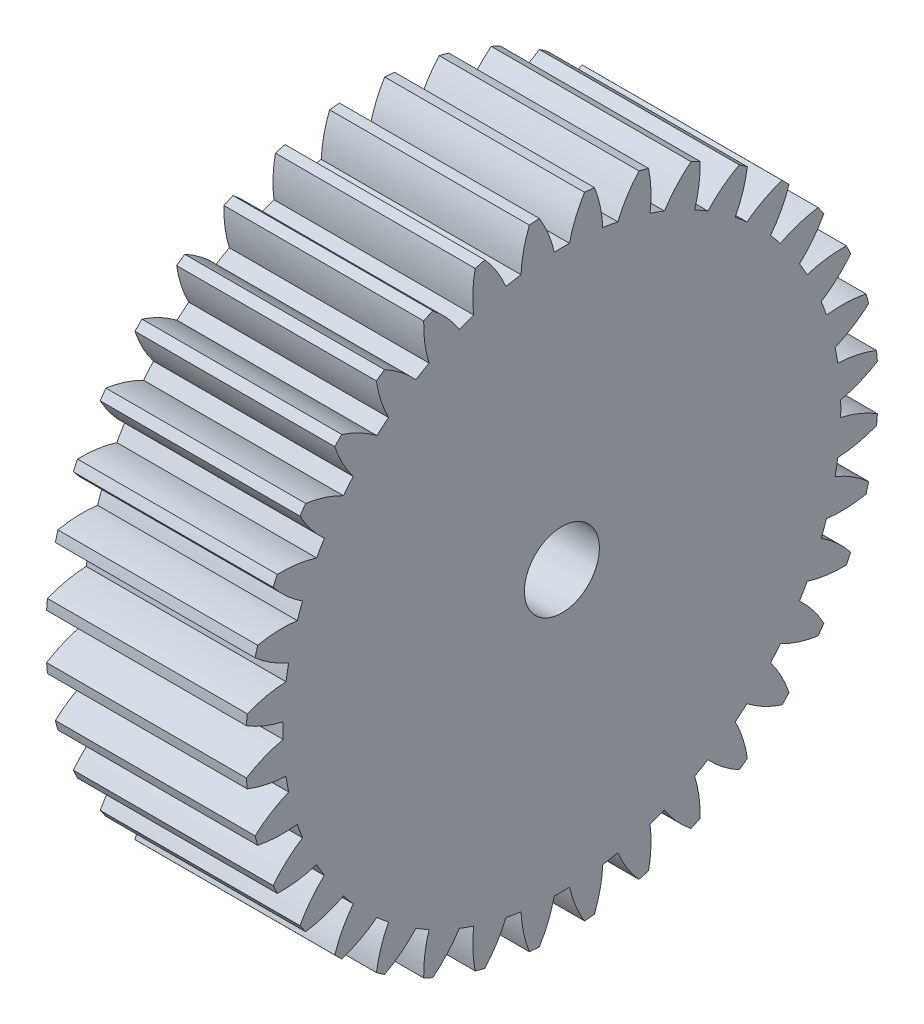
SolidWorks part; units mm, degrees
ref_plane "Plane1" through (0, 0, 0) normal (0, 0, 1) x (1, 0, 0)
ref_plane "Plane2" through (0, 0, 0) normal (0, 1, 0) x (1, 0, 0)
ref_plane "Plane3" through (0, 0, 0) normal (1, 0, 0) x (0, 0, -1)
other "Configuration Table"
sketch "HoldingSke" plane through (0, 0, 0) normal (0, 1, 0) x (1, 0, 0)
  line L0 (0, 0) -> (493.1768, -358.3139)
  line L1 (-15, 0) -> (100, 0) construction
  line L2 (0, 0) -> (-2.1039, 2.3779)
  line L3 (0, 0) -> (-11.863, 4.5341)
  line L4 (0, 0) -> (6.9867, 5.0761)
  line L5 (0, 0) -> (-47.5972, -17.7524)
  line L6 (0, 0) -> (-10.5278, -7.1032)
  line L7 (-2.1039, 2.3779) -> (8.8308, 51.9871)
  line L8 (-76.2, 54.61) -> (-71.1708, 54.61)
  line L9 (-71.009, 38.7566) -> (-53.1078, 45.2721)
  line L10 (-76.2, 71.12) -> (104.1128, 71.12)
  line L11 (0, 0) -> (-12.7, 0)
  line L12 (-76.2, 101.6) -> (-76.1573, 101.6)
  line L13 (24.9733, 27.94) -> (52.9518, 28.4284)
  line L14 (24.9733, 27.94) -> (25.0241, 27.9398)
  line L15 (24.9733, 27.94) -> (100.4021, 29.52)
  circle A0 centre (0, 0) radius 2.3812
  circle A1 centre (0, 0) radius 17.7292
  circle A2 centre (0, 0) radius 38.1
  circle A3 centre (0, 0) radius 2.3812
  dimension "MHD" = 35.4584
  dimension "Hub_dia" = 76.2
  dimension "Bore" = 4.7625
  dimension "MBD" = 4.7625
  dimension "Num_teeth" = 36
  dimension "Pitch" = 609.6
  dimension "Overall_len" = 50.8
  dimension "Show_teeth" = 36
  dimension "Thickness" = 12.7
  dimension "OAL" = 50.8001
  dimension "T_dim" = 5.0292
  dimension "Ap" = 20
  dimension "H" = 19.05
  dimension "Pitch_radius" = 180.3128
  dimension "Width" = 12.7
  dimension "Backlash" = 0.0427
  dimension "Addendum_fac" = 1
  dimension "Dedendum_fac" = 1.2
  dimension "Clearance_fac" = 0.2
  dimension "Dedendum_add" = 0.0508
sketch "BasProSke" plane through (0, 0, 0) normal (0, 1, 0) x (1, 0, 0)
  line L0 (-10, 0) -> (60, 0) construction
  line L1 (0, 0) -> (0, 20.1083)
  line L2 (0, 0) -> (12.7, 0)
  line L3 (12.7, 0) -> (12.7, 20.1083)
  line L4 (12.7, 20.1083) -> (0, 20.1083)
  dimension "Thickness" = 12.7
  dimension "Diameter" = 40.2167
revolve "Base-Revolve" add sketch "BasProSke" angle 360 about L0
sketch "TooCutSke" plane through (0, 0, 0) normal (1, 0, 0) x (0, 0, -1)
  line L1 (0, 0) -> (0, 107) construction
  line L2 (0, 0) -> (-0.9056, 19.0285) construction
  line L3 (0, 0) -> (-3.318, 37.9251) construction
  line L4 (-0.9056, 19.0285) -> (-1.659, 18.9625) construction
  arc A0 (0.4859, 17.7225) -> (-0.4859, 17.7225) centre (0, 0) ccw
  arc A1 (1.4524, 20.0813) -> (-1.4524, 20.0813) centre (0, 0) ccw
  circle A2 centre (0, 0) radius 19.05 construction
  circle A3 centre (0, 0) radius 17.9011 construction
  arc A4 (-0.4859, 17.7225) -> (-1.4524, 20.0813) centre (-7.9208, 16.0534) ccw
  arc A5 (1.4524, 20.0813) -> (0.4859, 17.7225) centre (7.9208, 16.0534) ccw
  dimension "Root_dia" = 35.4584
  dimension "Overcut_dia" = 40.2675
  dimension "Pitch_dia" = 38.1
  dimension "Base_dia" = 35.8023
  dimension "Flank_rad" = 7.62
  dimension "Half_ang" = 5
  dimension "Half_CT" = 0.7563
extrude "ToothCut" cut sketch "TooCutSke" along normal through all
fillet "Breaks" [suppressed] radius 0.0212
fillet "RootFillets" [suppressed] radius 0.2625
pattern_circular "TeethCuts" count 36 every 10 about axis through (-10, 0, 0) along (1, 0, 0) of "ToothCut", "RootFillets", "Breaks"
sketch "HubNeaOneSke" plane through (0, 0, 0) normal (-1, 0, 0) x (0, 0, 1)
  circle A0 centre (0, 0) radius 17.7292
  dimension "Diameter" = 35.4584
extrude "HubNearOne" [suppressed] add sketch "HubNeaOneSke" along normal blind 38.1001
sketch "HubNeaBotSke" plane through (0, 0, 0) normal (-1, 0, 0) x (0, 0, 1)
  circle A0 centre (0, 0) radius 17.7292
  dimension "Diameter" = 35.4584
extrude "HubNearBoth" [suppressed] add sketch "HubNeaBotSke" along normal blind 19.05
ref_plane "FarPln" through (12.7, 0, 0) normal (1, 0, 0) x (0, 0, -1)
sketch "HubFarSke" plane through (12.7, 0, 0) normal (1, 0, 0) x (0, 0, -1)
  circle A0 centre (0, 0) radius 17.7292
  dimension "Diameter" = 35.4584
extrude "HubFar" [suppressed] add sketch "HubFarSke" along normal blind 19.05
sketch "BorSke" plane through (0, 0, 0) normal (1, 0, 0) x (0, 0, -1)
  circle A0 centre (0, 0) radius 2.3812
  dimension "Diameter" = 4.7625
extrude "Bore" cut sketch "BorSke" along normal mid plane 101.6001
sketch "KeySke" plane through (0, 0, 0) normal (1, 0, 0) x (0, 0, -1)
  line L0 (-0.127, 0) -> (-0.127, 2.6479)
  line L1 (-0.127, 2.6479) -> (0.127, 2.6479)
  line L2 (0.127, 2.6479) -> (0.127, 0)
  line L3 (0, 0) -> (0, 34) construction
  line L4 (-0.127, 0) -> (0.127, 0)
  dimension "Offset" = 2.648
  dimension "Width" = 0.254
extrude "Keyway" [suppressed] cut sketch "KeySke" along normal mid plane 101.6001
pattern_circular "Keyway2" [suppressed] count 2 every 90 about axis through (-10, 0, 0) along (1, 0, 0)
equation "' \"Pitch@HoldingSke\" = 4"
equation "' \"Num_teeth@HoldingSke\" = 12"
equation "' \"Ap@HoldingSke\" =  20"
equation "' \"Ap@HoldingSke\" = 20"
equation "' \"Width@HoldingSke\" = 0.5"
equation "' \"Hub_dia@HoldingSke\"= 1"
equation "' \"Hub_dia@HoldingSke\" = 1"
equation "' \"Overall_len@HoldingSke\" = 1.0"
equation "' \"Bore@HoldingSke\" = 0.75"
equation "' \"T_dim@HoldingSke\" = 0.85"
equation "' \"Width@KeySke\" = 0.25"
equation "' \"Show_teeth@HoldingSke\" = 13"
equation "' \"Backlash@HoldingSke\" = 0.009"
equation "' \"Addendum_fac@HoldingSke\" = 1.0"
equation "' \"Dedendum_fac@HoldingSke\" = 1.25"
equation "' \"Dedendum_add@HoldingSke\" = 0.00005"
equation "' \"Clearance_fac@HoldingSke\" = 0.25"
equation "' \"Pitch@HoldingSke\" = 0.5"
equation "' \"Num_teeth@HoldingSke\" = 23"
equation "' \"Show_teeth@HoldingSke\" = 23"
equation "' \"Backlash@HoldingSke\" = 0.0375"
equation "\"Overcut_dia@TooCutSke\" = (\"Num_teeth@HoldingSke\" + 2 * \"Addendum_fac@HoldingSke\") / \"Pitch@HoldingSke\" + 0.002"
equation "\"Pitch_dia@TooCutSke\" = \"Num_teeth@HoldingSke\" / \"Pitch@HoldingSke\""
equation "\"Base_dia@TooCutSke\" = \"Num_teeth@HoldingSke\" / \"Pitch@HoldingSke\" * cos((\"Ap@HoldingSke\"  * 3.14159265 / 180))"
equation "\"Root_dia@TooCutSke\" = (\"Num_teeth@HoldingSke\" + 2) / \"Pitch@HoldingSke\" - 2 * (\"Addendum_fac@HoldingSke\" + \"Dedendum_fac@HoldingSke\") / \"Pitch@HoldingSke\" - \"Dedendum_add@HoldingSke\" * 2"
equation "\"Half_ang@TooCutSke\" = 180 / \"Num_teeth@HoldingSke\""
equation "\"Half_CT@TooCutSke\" = \"Num_teeth@HoldingSke\" / \"Pitch@HoldingSke\" * sin((3.14159265 / 2 / \"Num_teeth@HoldingSke\")) / 2 - 7 * \"Backlash@HoldingSke\" / 4"
equation "\"Flank_rad@TooCutSke\" = \"Num_teeth@HoldingSke\" / \"Pitch@HoldingSke\" / 5"
equation "\"Radius@RootFillets\" = \"Clearance_fac@HoldingSke\" / \"Pitch@HoldingSke\" + \"Dedendum_add@HoldingSke\""
equation "\"Break_rad@Breaks\" = 0.02 / \"Pitch@HoldingSke\""
equation "\"Thickness@HoldingSke\" = \"Width@HoldingSke\""
equation "\"OAL@HoldingSke\" = \"Thickness@HoldingSke\""
equation "\"MHD@HoldingSke\" = (\"Num_teeth@HoldingSke\" + 2) / \"Pitch@HoldingSke\" - 2 * (\"Addendum_fac@HoldingSke\" + \"Dedendum_fac@HoldingSke\")  / \"Pitch@HoldingSke\" - \"Dedendum_add@HoldingSke\" * 2"
equation "\"MBD@HoldingSke\" = (\"Num_teeth@HoldingSke\" + 2) / \"Pitch@HoldingSke\" - 2 * (\"Addendum_fac@HoldingSke\" + \"Dedendum_fac@HoldingSke\")  / \"Pitch@HoldingSke\" - \"Dedendum_add@HoldingSke\" * 2 - 0.002"
equation "\"MHD@HoldingSke\" = ((sgn( \"MHD@HoldingSke\" - \"Hub_dia@HoldingSke\" )-1)*( \"MHD@HoldingSke\" - \"Hub_dia@HoldingSke\" ))/-2+ \"Hub_dia@HoldingSke\""
equation "\"MBD@HoldingSke\" = ((sgn( \"MBD@HoldingSke\" - \"Bore@HoldingSke\" )-1)*( \"MBD@HoldingSke\" - \"Bore@HoldingSke\" ))/-2+ \"Bore@HoldingSke\""
equation "\"OAL@HoldingSke\" = ((sgn( \"OAL@HoldingSke\" - \"Overall_len@HoldingSke\" )+1)*( \"OAL@HoldingSke\" - \"Overall_len@HoldingSke\" ))/2 + \"Overall_len@HoldingSke\" + 0.000002"
equation "\"Num_teeth@TeethCuts\" = int( \"Show_teeth@HoldingSke\" ) + 1"
equation "\"Num_teeth@TeethCuts\" = ((sgn( \"Num_teeth@TeethCuts\" - \"Num_teeth@HoldingSke\" )-1)*( \"Num_teeth@TeethCuts\" - \"Num_teeth@HoldingSke\" ))/-2+ \"Num_teeth@HoldingSke\""
equation "\"Num_teeth@TeethCuts\" = ((sgn( \"Num_teeth@TeethCuts\" - 2.0)+1)*( \"Num_teeth@TeethCuts\" - 2.0))/2 +2.0"
equation "\"Angle@TeethCuts\" = 360.0 / \"Num_teeth@HoldingSke\""
equation "\"Diameter@BasProSke\" = (\"Num_teeth@HoldingSke\" + 2 * \"Addendum_fac@HoldingSke\") / \"Pitch@HoldingSke\""
equation "\"Thickness@BasProSke\"  = \"Thickness@HoldingSke\""
equation "' \"Fillet_rad@BasProSke\" =  \"Thickness@HoldingSke\" * 0.05"
equation "' \"Fillet_rad@BasProSke\" = \"Thickness@HoldingSke\" * 0.05"
equation "\"MHD@HoldingSke\" = ((sgn( \"MHD@HoldingSke\" - \"Root_dia@TooCutSke\" )-1)*( \"MHD@HoldingSke\" - \"Root_dia@TooCutSke\" ))/-2+ \"Root_dia@TooCutSke\""
equation "\"Diameter@HubNeaOneSke\" = \"MHD@HoldingSke\""
equation "\"Length@HubNearOne\" = \"OAL@HoldingSke\" - \"Thickness@BasProSke\""
equation "\"Diameter@HubNeaBotSke\" = \"MHD@HoldingSke\""
equation "\"Length@HubNearBoth\" = ( \"OAL@HoldingSke\" - \"Thickness@BasProSke\" ) / 2.0"
equation "\"Thickness@FarPln\" = \"Thickness@BasProSke\""
equation "\"Diameter@HubFarSke\" = \"MHD@HoldingSke\""
equation "\"Length@HubFar\" = ( \"OAL@HoldingSke\" - \"Thickness@BasProSke\" ) / 2.0"
equation "\"Diameter@BorSke\" = \"MBD@HoldingSke\""
equation "\"D1@Bore\" = \"OAL@HoldingSke\" * 2.0"
equation "\"D1@Keyway\" = \"OAL@HoldingSke\" * 2.0"
equation "\"Offset@KeySke\" = \"T_dim@HoldingSke\" - \"MBD@HoldingSke\" / 2.0"
